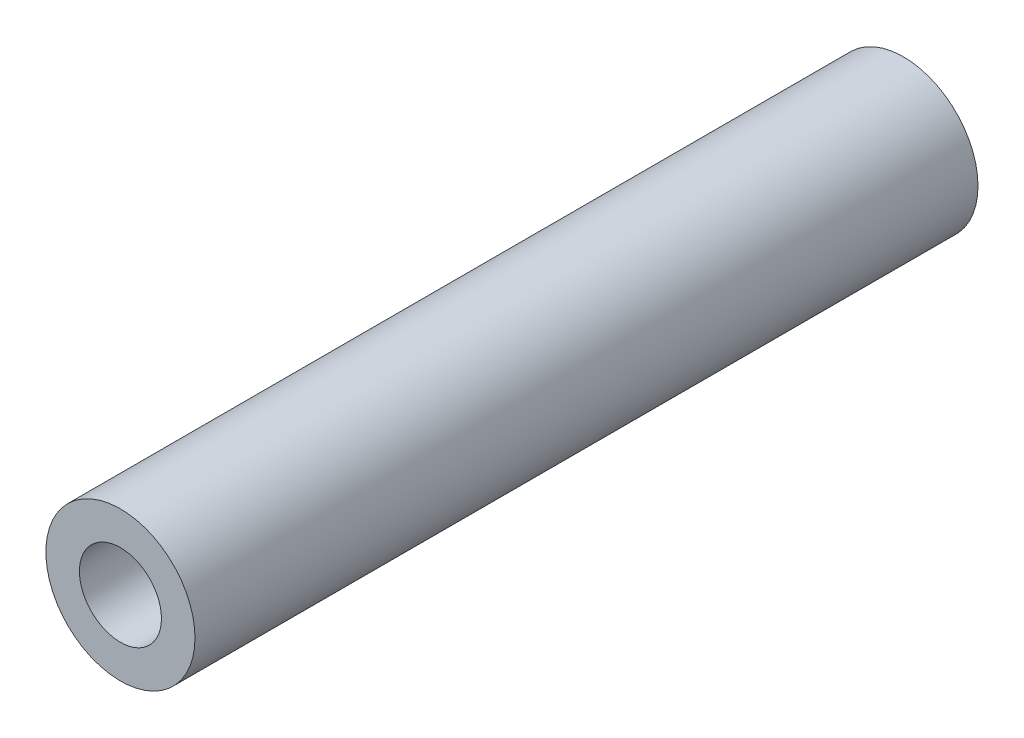
SolidWorks part; units mm, degrees
material "6061 合金"
ref_plane "前视基准面" through (0, 0, 0) normal (0, 0, 1) x (1, 0, 0)
ref_plane "上视基准面" through (0, 0, 0) normal (0, 1, 0) x (1, 0, 0)
ref_plane "右视基准面" through (0, 0, 0) normal (1, 0, 0) x (0, 0, -1)
sketch "草图1" plane through (0, 0, 0) normal (0, 0, 1) x (1, 0, 0)
  circle A1 centre (0, 0) radius 3
  dimension "D1" = 6
extrude "凸台-拉伸1" add sketch "草图1" along normal blind 31.5
hole_wizard "M4 螺纹孔1" positions "草图2" profile "草图3" tap size "M4" standard "GB" end condition through all
sketch "草图2" plane through (0, 0, 31.5) normal (0, 0, 1) x (1, 0, 0)
  point P0 (0, 0)
sketch "草图3" plane through (0, 0, 31.5) normal (1, 0, 0) x (0, -1, 0)
  line L0 (0, 0) -> (0, 31.5)
  line L1 (0, 31.5) -> (1.65, 31.5)
  line L2 (1.65, 31.5) -> (1.65, 0)
  line L5 (1.65, 0) -> (0, 0)
  line L11 (0, -6.35) -> (0, 107.95) construction
  dimension "通孔螺纹孔钻头直径" = 3.3
  dimension "通孔螺纹孔钻头深度" = 31.5
cosmetic thread "孔螺蚊线1" parameters "D2"=4
